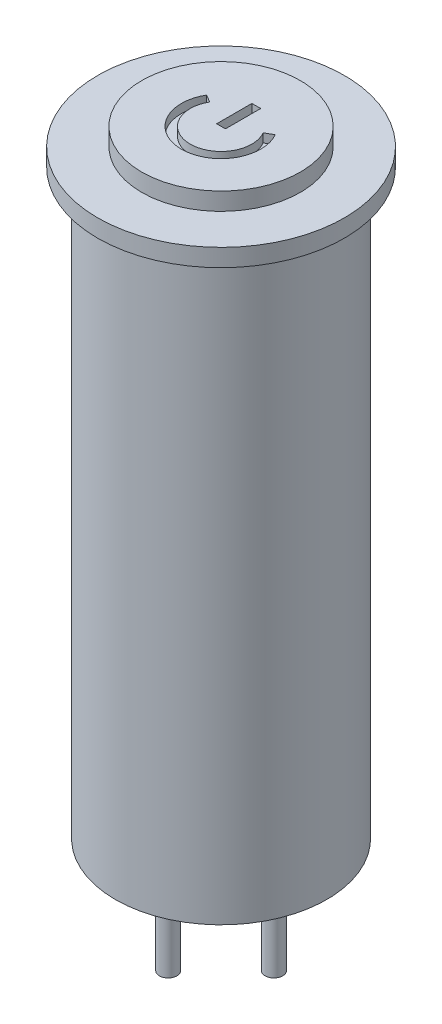
SolidWorks part; units mm, degrees
ref_plane "前视基准面" through (0, 0, 0) normal (0, 0, 1) x (1, 0, 0)
ref_plane "上视基准面" through (0, 0, 0) normal (0, 1, 0) x (1, 0, 0)
ref_plane "右视基准面" through (0, 0, 0) normal (1, 0, 0) x (0, 0, -1)
other "Configuration Table"
sketch "草图1" plane through (0, 0, 0) normal (0, 1, 0) x (1, 0, 0)
  circle A0 centre (0, 0) radius 7
  dimension "D1" = 14
extrude "凸台-拉伸1" add sketch "草图1" along normal blind 1
sketch "草图2" plane through (0, 1, 0) normal (0, 1, 0) x (1, 0, 0)
  circle A0 centre (0, 0) radius 4.5
  dimension "D1" = 9
extrude "凸台-拉伸2" add sketch "草图2" along normal blind 1
sketch "草图3" plane through (0, 2, 0) normal (0, 1, 0) x (1, 0, 0)
  line L0 (0, 0) -> (0, 2)
  arc A0 (-1.7321, 1) -> (1.7321, 1) centre (0, 0) ccw
  point P5 (-1.2801, 0.706)
  point P6 (1.7534, 0.9659)
  point P7 (0, 1)
  point P8 (0, 0)
  point P9 (0, 0)
  dimension "D2" = 2
  dimension "D1" = 2
extrude "切除-拉伸-薄壁1" cut sketch "草图3" against normal blind 0.5 thin thin type mid plane wall 0.5
sketch "草图4" plane through (0, 0, 0) normal (0, -1, 0) x (1, 0, 0)
  circle A0 centre (0, 0) radius 6
  dimension "D1" = 12
extrude "凸台-拉伸3" add sketch "草图4" along normal blind 33
sketch "草图5" plane through (0, -33, 0) normal (0, -1, 0) x (1, 0, 0)
  circle A0 centre (0, 3) radius 0.5
  circle A1 centre (3, 0) radius 0.5
  circle A2 centre (0, -3) radius 0.5
  circle A3 centre (-3, 0) radius 0.5
  point P12 (0, 0)
  dimension "D2" = 1
  dimension "D1" = 3
  dimension "D3" = 4
extrude "凸台-拉伸4" add sketch "草图5" along normal blind 5
